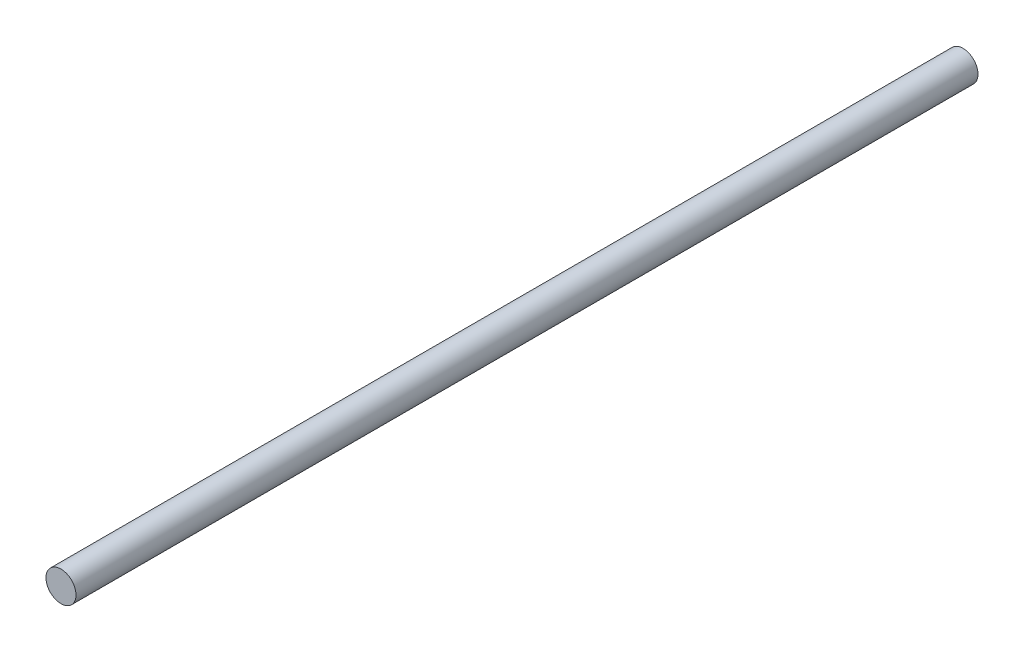
SolidWorks part; units mm, degrees
material "AISI 316 Stainless Steel Sheet (SS)"
ref_plane "Front Plane" through (0, 0, 0) normal (0, 0, 1) x (1, 0, 0)
ref_plane "Top Plane" through (0, 0, 0) normal (0, 1, 0) x (1, 0, 0)
ref_plane "Right Plane" through (0, 0, 0) normal (1, 0, 0) x (0, 0, -1)
sketch "Sketch1" plane through (0, 0, 0) normal (0, 0, 1) x (1, 0, 0)
  line L0 (-23.8067, 0) -> (23.8067, 0) construction
  line L1 (0, 19.3486) -> (0, -19.3486) construction
  circle A0 centre (0, 0) radius 5
  point P8 (0, 0)
  point P14 (0, 0)
  dimension "D1" = 10
extrude "Boss-Extrude1" add sketch "Sketch1" against normal blind 300.5
